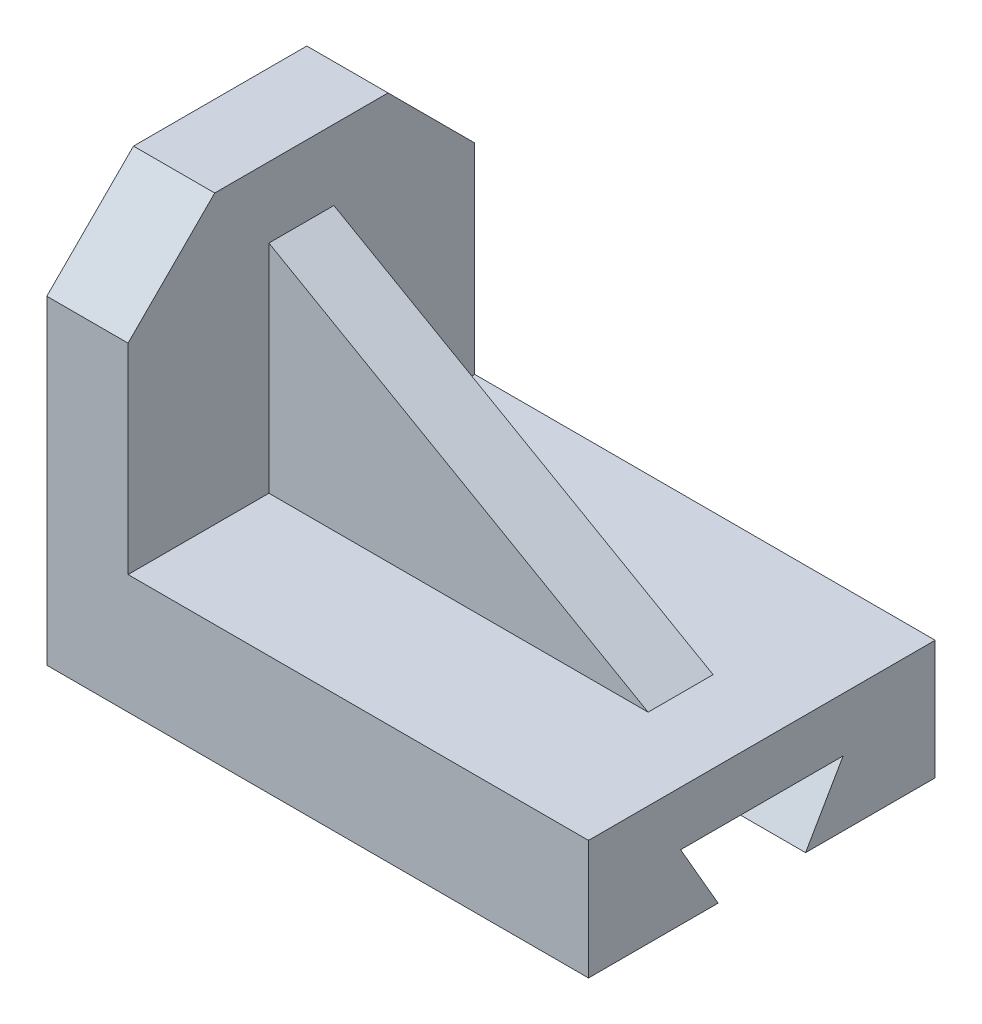
SolidWorks part; units mm, degrees
ref_plane "Front Plane" through (0, 0, 0) normal (0, 0, 1) x (1, 0, 0)
ref_plane "Top Plane" through (0, 0, 0) normal (0, 1, 0) x (1, 0, 0)
ref_plane "Right Plane" through (0, 0, 0) normal (1, 0, 0) x (0, 0, -1)
sketch "Sketch1" plane through (0, 0, 0) normal (0, 1, 0) x (1, 0, 0)
  line L0 (0, 131.541) -> (0, -67.541) construction
  line L1 (-104.3934, 0) -> (4.3934, 0) construction
  line L2 (-50, 32) -> (-50, -32)
  line L3 (-50, -32) -> (50, -32)
  line L4 (50, -32) -> (50, 32)
  line L5 (50, 32) -> (-50, 32)
  point P5 (0, 32)
  point P9 (-50, 0)
  point P11 (0, 32)
  dimension "D1" = 64
  dimension "D2" = 100
extrude "Boss-Extrude1" add sketch "Sketch1" along normal blind 22
sketch "Sketch2" plane through (-50, 0, 0) normal (-1, 0, 0) x (0, 0, 1)
  line L0 (-32, 22) -> (-32, 59)
  line L1 (-32, 59) -> (-16, 75)
  line L2 (-16, 75) -> (16, 75)
  line L3 (16, 75) -> (32, 59)
  line L4 (32, 59) -> (32, 22)
  line L5 (32, 22) -> (-32, 22)
  line L6 (-32, 0) -> (32, 0) construction
  dimension "D1" = 37
  dimension "D2" = 37
  dimension "D3" = 75
  dimension "D4" = 16
  dimension "D5" = 16
extrude "Boss-Extrude2" add sketch "Sketch2" against normal blind 15
sketch "Sketch3" plane through (50, 0, 0) normal (1, 0, 0) x (0, 0, -1)
  line L0 (-8.0718, 0) -> (-15, 12)
  line L1 (-32, 0) -> (32, 0) construction
  line L2 (-15, 12) -> (15, 12)
  line L3 (15, 12) -> (8.0718, 0)
  line L4 (8.0718, 0) -> (-8.0718, 0)
  point P5 (0, 0)
  dimension "D1" = 30
  dimension "D2" = 60
  dimension "D3" = 60
  dimension "D4" = 12
extrude "Cut-Extrude2" cut sketch "Sketch3" against normal through all
sketch "Sketch5" plane through (0, 0, 0) normal (0, 0, 1) x (1, 0, 0)
  line L0 (-35, 62) -> (35, 22)
  line L2 (-35, 59) -> (-35, 75) construction
  line L3 (-35, 22) -> (50, 22) construction
  point P7 (0, 0)
  point P8 (0, 0)
  point P9 (0, 0)
  dimension "D1" = 40
  dimension "D2" = 70
rib "Rib1" sketch "Sketch5" sketch "Sketch5" thickness 12 extrusion direction parallel to sketch draft on no parameters "D1"=12
